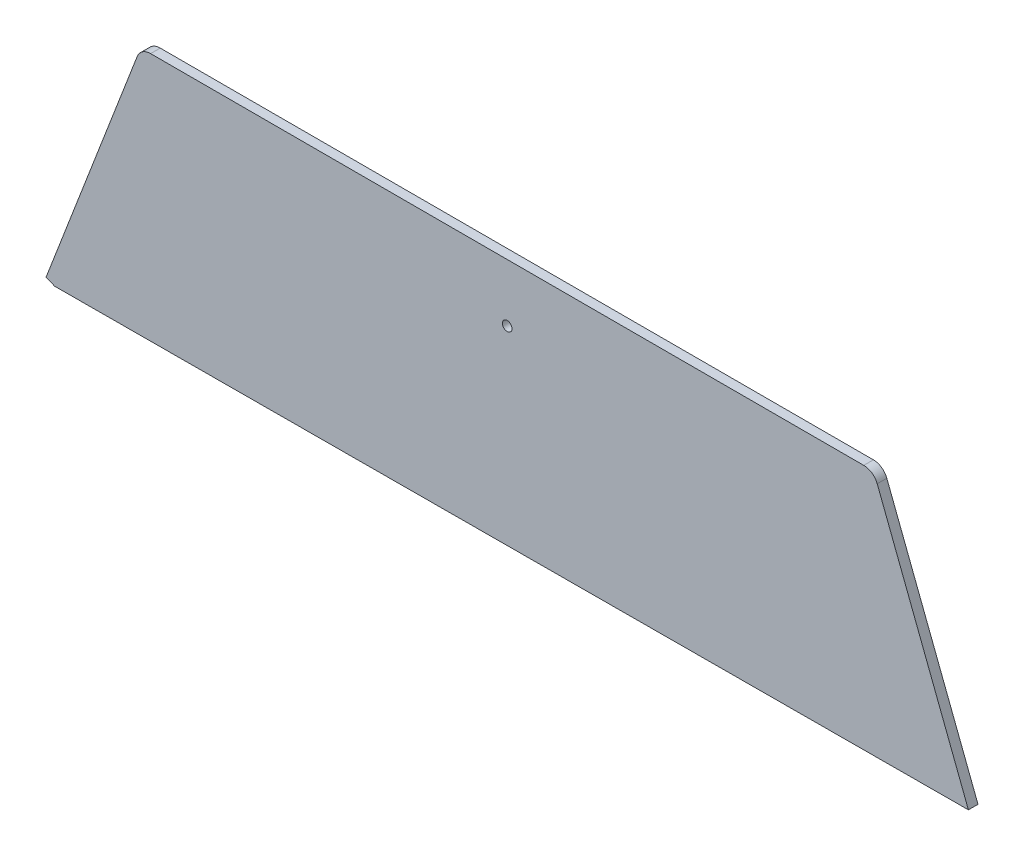
SolidWorks part; units mm, degrees
ref_plane "Front Plane" through (0, 0, 0) normal (0, 0, 1) x (1, 0, 0)
ref_plane "Top Plane" through (0, 0, 0) normal (0, 1, 0) x (1, 0, 0)
ref_plane "Right Plane" through (0, 0, 0) normal (1, 0, 0) x (0, 0, -1)
sketch "Sketch1" plane through (0, 0, 0) normal (0, 0, 1) x (1, 0, 0)
  line L0 (94.1165, -51.2814) -> (96.1165, -51.2814)
  line L1 (75.3713, -2.5927) -> (94.1165, -51.2814)
  line L2 (77.1131, -1.9221) -> (96.1165, -51.2814)
  line L3 (25, 0) -> (74.3134, 0)
  line L4 (-74.3134, -1.8665) -> (74.3134, -1.8665)
  line L5 (-74.3134, 0) -> (-25, 0)
  line L6 (-96.1165, -51.2814) -> (-77.1131, -1.9221)
  line L7 (-94.2948, -51.9828) -> (-75.2467, -2.5072)
  line L8 (-96.1165, -51.2814) -> (-94.2948, -51.9828)
  line L9 (25, 0) -> (-25, 0)
  line L10 (-94.2948, -51.9828) -> (94.1165, -51.2814)
  arc A0 (77.1131, -1.9221) -> (74.3134, 0) centre (74.3134, -3) ccw
  arc A1 (75.3713, -2.5927) -> (74.3134, -1.8665) centre (74.3134, -3) ccw
  arc A2 (-77.1131, -1.9221) -> (-74.3134, 0) centre (-74.3134, -3) cw
  arc A3 (-75.2467, -2.5072) -> (-74.3134, -1.8665) centre (-74.3134, -2.8665) cw
  point P18 (0, 0)
  dimension "D4" = 3
  dimension "D8" = 3
  dimension "D10" = 1
  dimension "D12" = 1.952
  dimension "D1" = 192.2329
  dimension "D2" = 148.6269
  dimension "D3" = 49.3134
  dimension "D5" = 49.3593
  dimension "D6" = 52.8911
  dimension "D7" = 49.3134
  dimension "D9" = 52.8911
  dimension "D11" = 2
  dimension "D13" = 1.8217
extrude "Boss-Extrude1" add sketch "Sketch1" along normal blind 2 contours A3 L7 L10 L1 A1 L4 | L7 A3 L4 A1 L1 L0 L2 A0 L3 L9 L5 A2 L6 L8
sketch "Sketch2" plane through (0, 0, 2) normal (0, 0, 1) x (1, 0, 0)
  line L0 (0, 0) -> (0, -12) construction
  line L1 (-74.3134, 0) -> (74.3134, 0) construction
  circle A0 centre (0, -12) radius 1
  dimension "D2" = 2
  dimension "D1" = 12
extrude "Cut-Extrude1" cut sketch "Sketch2" against normal blind 10
